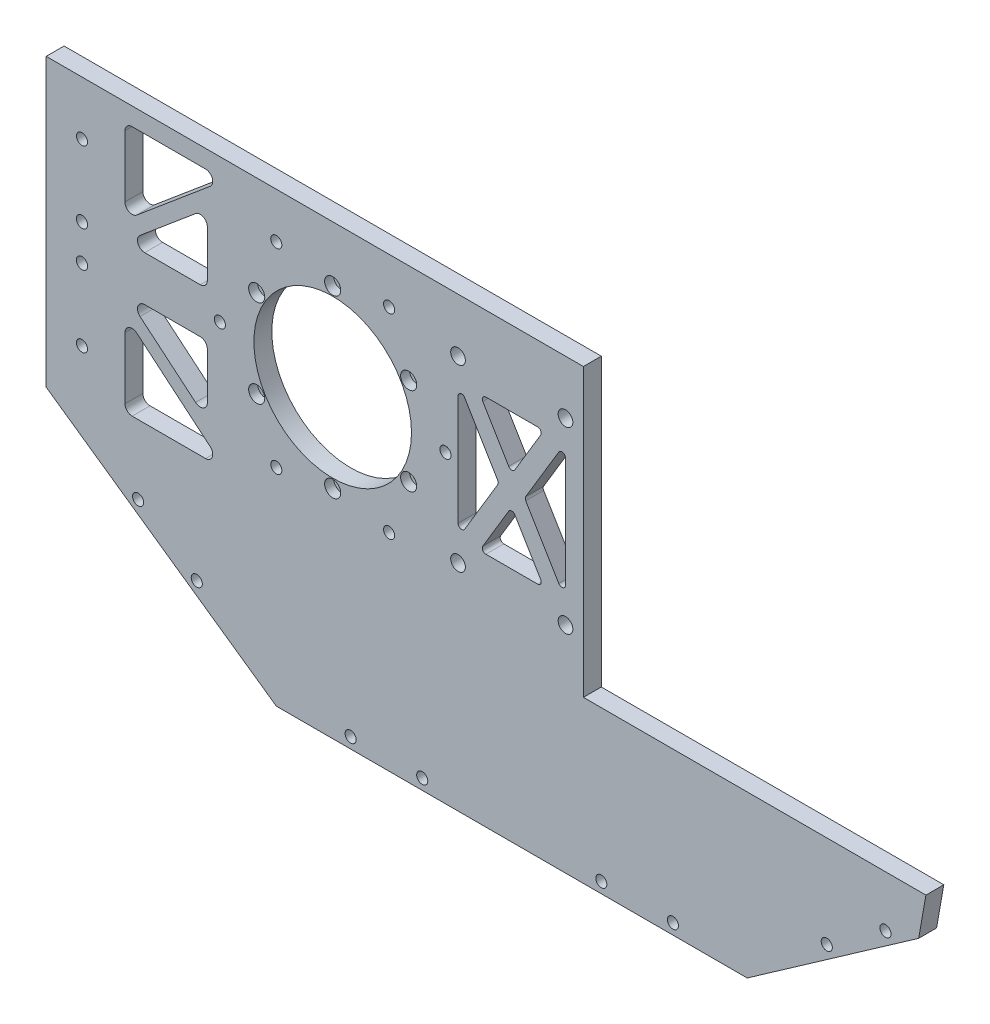
SolidWorks part; units mm, degrees
ref_plane "前视基准面" through (0, 0, 0) normal (0, 0, 1) x (1, 0, 0)
ref_plane "上视基准面" through (0, 0, 0) normal (0, 1, 0) x (1, 0, 0)
ref_plane "右视基准面" through (0, 0, 0) normal (1, 0, 0) x (0, 0, -1)
sketch "草图1" plane through (0, 0, 0) normal (0, 0, 1) x (1, 0, 0)
  line L1 (-80, 40) -> (70, 40)
  line L2 (-80, 40) -> (-80, -40)
  line L3 (-80, -40) -> (70, -40)
  line L4 (70, 40) -> (70, -40)
  circle A0 centre (0, 0) radius 24.5 construction
  circle A1 centre (0, -24.5) radius 1.3
  circle A2 centre (-21.2176, -12.25) radius 1.3
  circle A3 centre (-21.2176, 12.25) radius 1.3
  circle A4 centre (0, 0) radius 22
  circle A5 centre (0, 24.5) radius 1.3
  circle A6 centre (21.2176, 12.25) radius 1.3
  circle A7 centre (21.2176, -12.25) radius 1.3
  point P11 (0, 0)
  point P15 (70, 0)
  dimension "D1" = 49
  dimension "D2" = 2.6
  dimension "D4" = 44
  dimension "D5" = 80
  dimension "D6" = 70
  dimension "D7" = 80
  dimension "D3" = 6
extrude "凸台-拉伸1" add sketch "草图1" along normal blind 5
sketch "草图3" plane through (0, 0, 5) normal (0, 0, 1) x (1, 0, 0)
  line L0 (0, 0) -> (-70, 0) construction
  line L1 (-70, 0) -> (-70, -25) construction
  line L3 (-70, 0) -> (-70, 24.3133)
  circle A4 centre (-70, -25) radius 1.55
  circle A5 centre (-70, -5) radius 1.5828
  circle A6 centre (-70, 25) radius 1.55
  circle A7 centre (-70, 5) radius 1.5828
  point P6 (-70, 0)
  dimension "D3" = 3.1
  dimension "D4" = 20
  dimension "D1" = 70
  dimension "D2" = 25
extrude "切除-拉伸3" cut sketch "草图3" against normal blind 12.5
sketch "草图4" plane through (0, 0, 5) normal (0, 0, 1) x (1, 0, 0)
  line L0 (-58, 35) -> (-30, 35)
  line L1 (-30, 35) -> (-58, 11.5052)
  line L2 (-58, 11.5052) -> (-58, 35)
  line L3 (-35, 25.5829) -> (-58, 6.2836)
  line L4 (-58, 6.2836) -> (-35, 6.2836)
  line L5 (-35, 6.2836) -> (-35, 25.5829)
  line L8 (70, 40) -> (-80, 40) construction
  line L9 (-80, 40) -> (-80, -40) construction
  dimension "D1" = 5
  dimension "D2" = 22
  dimension "D3" = 140
  dimension "D4" = 45
  dimension "D6" = 4
extrude "切除-拉伸5" cut sketch "草图4" against normal blind 8 contours L2 L0 L1 | L5 L3 L4
fillet "圆角3" radius 2 6 edges at (-35, 6.2836, 2.5) (-58, 6.2836, 2.5) (-35, 25.5829, 2.5) (-30, 35, 2.5) (-58, 11.5052, 2.5) (-58, 35, 2.5)
mirror "镜向2" about plane through (0, 0, 0) normal (0, 1, 0) of "圆角3", "切除-拉伸5"
sketch "草图10" plane through (0, 0, 5) normal (0, 0, 1) x (1, 0, 0)
  line L0 (-80, -40) -> (-127.0531, -7.0531)
  line L1 (-127.0531, -7.0531) -> (-80, 40)
  line L2 (-80, -40) -> (70, -40) construction
  line L3 (-80, 40) -> (-80, -40) construction
  line L4 (-80, 40) -> (-80, -40)
  dimension "D1" = 145
  dimension "D2" = 45
extrude "凸台-拉伸4" add sketch "草图10" against normal up to surface (5 mm away) contours L4 L0 L1 up to face at (-49.3474, 27.3903, 0)
fillet "圆角5" radius 5 1 edges at (-127.0531, -7.0531, 2.5)
sketch "草图11" plane through (0, 0, 5) normal (0, 0, 1) x (1, 0, 0)
  line L0 (0, 0) -> (0, 34) construction
  line L1 (0, 0) -> (-15.75, 27.2798)
  circle A0 centre (0, 0) radius 29 construction
  circle A1 centre (0, 0) radius 34 construction
  circle A2 centre (0, 0) radius 31.5 construction
  circle A3 centre (-15.75, 27.2798) radius 1.55
  circle A4 centre (15.75, 27.2798) radius 1.55
  circle A5 centre (31.5, 0) radius 1.55
  circle A6 centre (15.75, -27.2798) radius 1.55
  circle A7 centre (-15.75, -27.2798) radius 1.55
  circle A8 centre (-31.5, 0) radius 1.55
  point P20 (0, 0)
  dimension "D1" = 58
  dimension "D2" = 68
  dimension "D3" = 63
  dimension "D5" = 3.1
  dimension "D4" = 30
  dimension "D6" = 6
extrude "切除-拉伸7" cut sketch "草图11" against normal blind 25 contours A3 | A4 | A5 | A6 | A7 | A8
sketch "草图12" plane through (0, 0, 5) normal (0, 0, 1) x (1, 0, 0)
  line L0 (0, 0) -> (50, 0) construction
  line L6 (35, -25) -> (65, -25) construction
  line L7 (35, -25) -> (35, 25) construction
  line L8 (35, 25) -> (65, 25) construction
  line L9 (65, -25) -> (65, 25) construction
  line L10 (35, -25) -> (65, 25) construction
  line L11 (35, 25) -> (65, -25) construction
  circle A0 centre (0, 0) radius 28 construction
  circle A1 centre (35, 25) radius 2.05
  circle A2 centre (65, 25) radius 2.05
  circle A3 centre (65, -25) radius 2.05
  circle A4 centre (35, -25) radius 2.05
  dimension "D3" = 56
  dimension "D5" = 4.1
  dimension "D6" = 4.1
  dimension "D1" = 30
  dimension "D2" = 50
  dimension "D4" = 50
extrude "切除-拉伸8" cut sketch "草图12" against normal blind 10
sketch "草图13" plane through (0, 0, 5) normal (0, 0, 1) x (1, 0, 0)
  line L0 (35, 25) -> (65, -25) construction
  line L6 (35, 25) -> (65, -25) construction
  line L10 (35, 19) -> (35, -19)
  line L11 (35, -19) -> (46.4, 0)
  line L12 (46.4, 0) -> (35, 19)
  line L13 (35, -25) -> (65, 25) construction
  line L14 (50, 0) -> (50, -49.4768) construction
  line L15 (65, -19) -> (53.6, 0)
  line L16 (65, 19) -> (65, -19)
  line L17 (53.6, 0) -> (65, 19)
  line L18 (41, 19) -> (50, 4)
  line L19 (50, 4) -> (59, 19)
  line L20 (59, 19) -> (41, 19)
  line L21 (35, 19) -> (65, 19) construction
  line L22 (50, 0) -> (90.4004, 0) construction
  line L23 (50, -4) -> (59, -19)
  line L24 (41, -19) -> (50, -4)
  line L25 (59, -19) -> (41, -19)
  circle A0 centre (35, -25) radius 2.05 construction
  circle A1 centre (65, 25) radius 2.05 construction
  point P4 (50, 0)
  dimension "D1" = 6
  dimension "D2" = 6
  dimension "D3" = 6
  dimension "D4" = 6
  dimension "D5" = 0
extrude "切除-拉伸9" cut sketch "草图13" against normal blind 10
fillet "圆角6" radius 1 12 edges at (35, -19, 2.5) (46.4, 0, 2.5) (35, 19, 2.5) (41, -19, 2.5) (50, -4, 2.5) (59, -19, 2.5) (65, -19, 2.5) (65, 19, 2.5) (53.6, 0, 2.5) (50, 4, 2.5) (59, 19, 2.5) (41, 19, 2.5)
sketch "草图15" plane through (0, 0, 0) normal (0, 0, -1) x (-1, 0, 0)
  line L0 (-50, 19) -> (-50, -132.8609) construction
  line L2 (-57.2338, 19) -> (-42.7662, 19) construction
  line L3 (80, -40) -> (15.7333, -85)
  line L4 (15.7333, -85) -> (-115.7333, -85)
  line L5 (80, -40) -> (-70, -40) construction
  line L6 (122.1719, -10.4709) -> (80, -40) construction
  line L7 (80, -40) -> (-180, -40)
  line L8 (-50, -85) -> (-50, -40)
  line L9 (-180, -40) -> (-115.7333, -85)
  dimension "D1" = 180
  dimension "D2" = 45
extrude "凸台-拉伸5" add sketch "草图15" against normal up to surface (5 mm away) contours L8 L4 L3 L7 | L7 L9 L4 L8 up to face at (50, 13.974, 5)
chamfer "倒角1" distance 20 angle 45 1 edges at (180, -40, 2.5)
sketch "草图16" plane through (0, 0, 0) normal (0, 0, -1) x (-1, 0, 0)
  line L0 (-50, -85) -> (-50, -82)
  line L1 (15.7333, -85) -> (-115.7333, -85) construction
  line L2 (-50, -82) -> (-75, -82) construction
  line L3 (-50, -82) -> (-50, -114.8278) construction
  circle A0 centre (-75, -82) radius 1.55
  circle A1 centre (-95, -82) radius 1.55
  circle A2 centre (-25, -82) radius 1.55
  circle A3 centre (-5, -82) radius 1.55
  dimension "D3" = 3.1
  dimension "D1" = 3
  dimension "D2" = 25
  dimension "D4" = 2
extrude "切除-拉伸11" cut sketch "草图16" against normal blind 10.5 contours A1 | A0 | A2 | A3
sketch "草图17" plane through (0, 0, 5) normal (0, 0, 1) x (1, 0, 0)
  circle A0 centre (0, 24.5) radius 2.25
  circle A1 centre (21.2176, 12.25) radius 2.25
  circle A2 centre (21.2176, -12.25) radius 2.25
  circle A3 centre (0, -24.5) radius 2.25
  circle A4 centre (-21.2176, -12.25) radius 2.25
  circle A5 centre (-21.2176, 12.25) radius 2.25
  point P15 (0, 0)
  dimension "D1" = 4.5
  dimension "D2" = 6
extrude "切除-拉伸12" cut sketch "草图17" against normal blind 2.5
sketch "草图18" plane through (0, 0, 0) normal (0, 0, -1) x (-1, 0, 0)
  line L0 (-50, 19) -> (-50, -19)
  line L1 (-57.2338, 19) -> (-42.7662, 19) construction
  line L2 (-42.7662, -19) -> (-57.2338, -19) construction
  line L3 (-50, 0) -> (80, 0)
  line L4 (80, 0) -> (80, 40)
  line L5 (80, 40) -> (122.8396, -2.8396) construction
  line L6 (80, 0) -> (80, -40)
  line L7 (122.1719, -10.4709) -> (15.7333, -85) construction
  line L8 (80, -40) -> (122.1719, -10.4709)
  line L9 (80, 40) -> (122.8396, -2.8396)
  arc A0 (122.1719, -10.4709) -> (122.8396, -2.8396) centre (119.3041, -6.3751) ccw construction
  arc A1 (122.1719, -10.4709) -> (122.8396, -2.8396) centre (119.3041, -6.3751) ccw
  dimension "D1" = 130
extrude "切除-拉伸13" cut sketch "草图18" against normal blind 10 contours L8 A1 L9 L4 L6
sketch "草图19" plane through (0, 0, 5) normal (0, 0, 1) x (1, 0, 0)
  line L0 (-47.8667, -62.5) -> (-46.1459, -60.0425) construction
  line L1 (-15.7333, -85) -> (-80, -40) construction
  line L2 (-54.3375, -54.3068) -> (-37.9544, -65.7783) construction
  line L3 (50, 19) -> (50, -139.3499) construction
  line L4 (57.2338, 19) -> (42.7662, 19) construction
  circle A0 centre (-54.3375, -54.3068) radius 1.55
  circle A1 centre (-37.9544, -65.7783) radius 1.55
  circle A2 centre (137.9544, -65.7783) radius 1.55
  circle A3 centre (154.3375, -54.3068) radius 1.55
  point P7 (-46.1459, -60.0425)
  dimension "D3" = 3.1
  dimension "D4" = 3.1
  dimension "D1" = 3
  dimension "D2" = 20
extrude "切除-拉伸14" cut sketch "草图19" against normal blind 13
